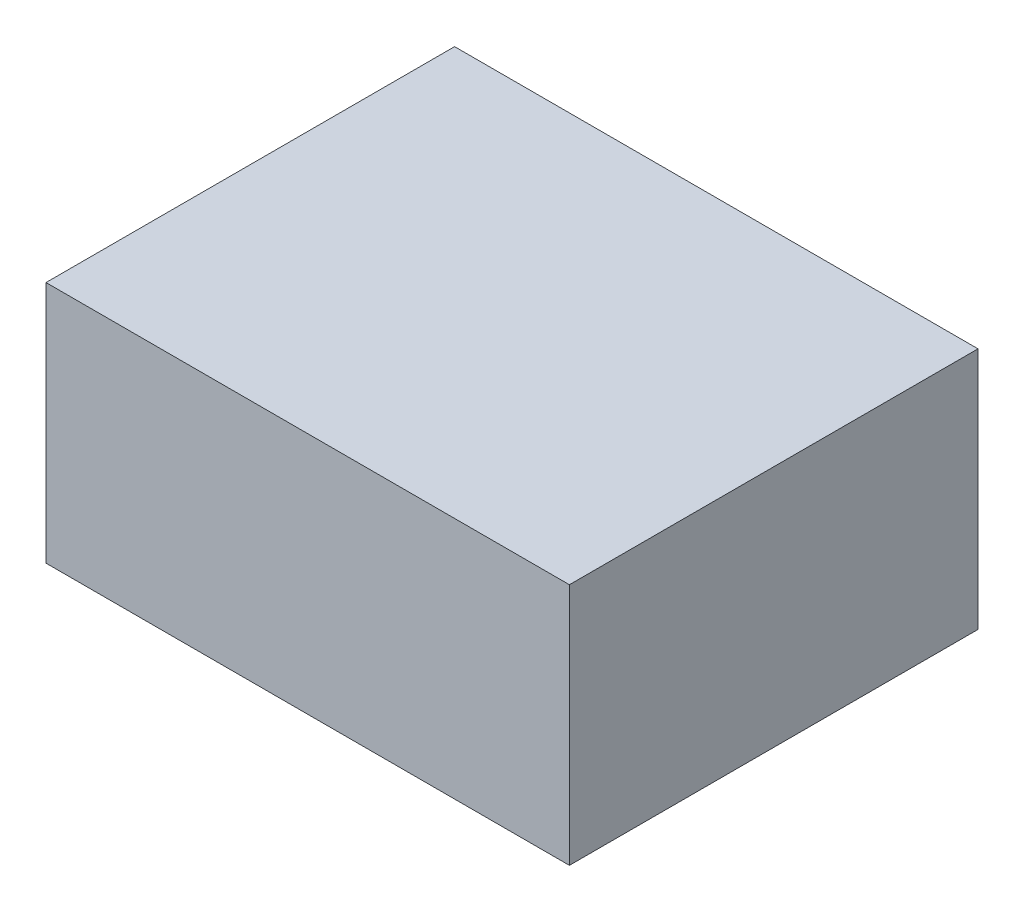
SolidWorks part; units mm, degrees
ref_plane "Front Plane" through (0, 0, 0) normal (0, 0, 1) x (1, 0, 0)
ref_plane "Top Plane" through (0, 0, 0) normal (0, 1, 0) x (1, 0, 0)
ref_plane "Right Plane" through (0, 0, 0) normal (1, 0, 0) x (0, 0, -1)
sketch "Sketch1" plane through (0, 0, 0) normal (0, 1, 0) x (1, 0, 0)
  line L1 (-53.8367, -42.0287) -> (53.8367, -42.0287)
  line L2 (-53.8367, -42.0287) -> (-53.8367, 42.0287)
  line L3 (-53.8367, 42.0287) -> (53.8367, 42.0287)
  line L4 (53.8367, -42.0287) -> (53.8367, 42.0287)
  line L5 (-53.8367, -42.0287) -> (53.8367, 42.0287) construction
  line L6 (-53.8367, 42.0287) -> (53.8367, -42.0287) construction
  point P0 (0, 0)
extrude "Boss-Extrude1" add sketch "Sketch1" along normal blind 50
